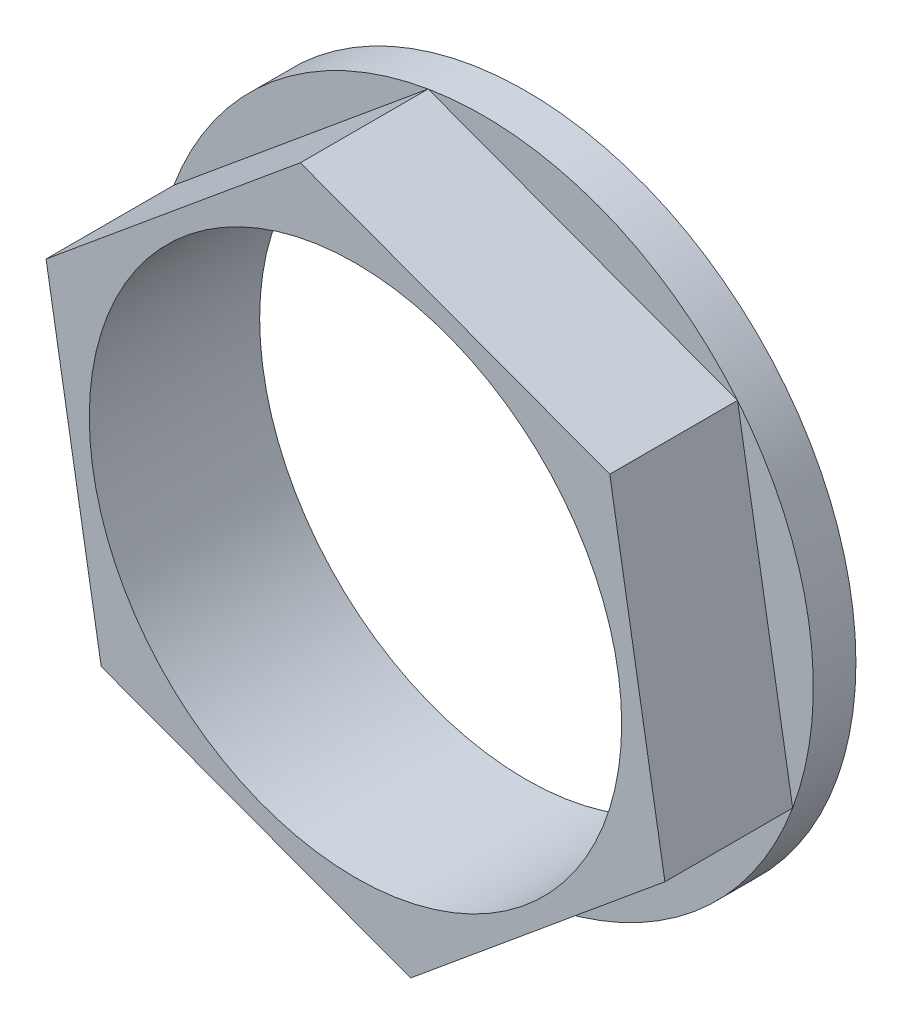
SolidWorks part; units mm, degrees
ref_plane "Plano frontal" through (0, 0, 0) normal (0, 0, 1) x (1, 0, 0)
ref_plane "Plano superior" through (0, 0, 0) normal (0, 1, 0) x (1, 0, 0)
ref_plane "Plano direito" through (0, 0, 0) normal (1, 0, 0) x (0, 0, -1)
sketch "Esboço1" plane through (0, 0, 0) normal (0, 0, 1) x (1, 0, 0)
  circle A0 centre (0, 0) radius 6.25
  circle A1 centre (0, 0) radius 7.75
  dimension "D1" = 12.5
  dimension "D2" = 15.5
extrude "Ressalto-extrusão1" add sketch "Esboço1" along normal blind 1
sketch "Esboço2" plane through (0, 0, 1) normal (0, 0, 1) x (1, 0, 0)
  line L1 (-7.2646, 2.6997) -> (-5.9703, -4.9415)
  line L2 (-5.9703, -4.9415) -> (1.2943, -7.6412)
  line L3 (1.2943, -7.6412) -> (7.2646, -2.6997)
  line L4 (7.2646, -2.6997) -> (5.9703, 4.9415)
  line L5 (5.9703, 4.9415) -> (-1.2943, 7.6412)
  line L6 (-1.2943, 7.6412) -> (-7.2646, 2.6997)
  circle A0 centre (0, 0) radius 6.7117 construction
  circle A1 centre (0, 0) radius 6.25
extrude "Ressalto-extrusão2" add sketch "Esboço2" along normal blind 3
